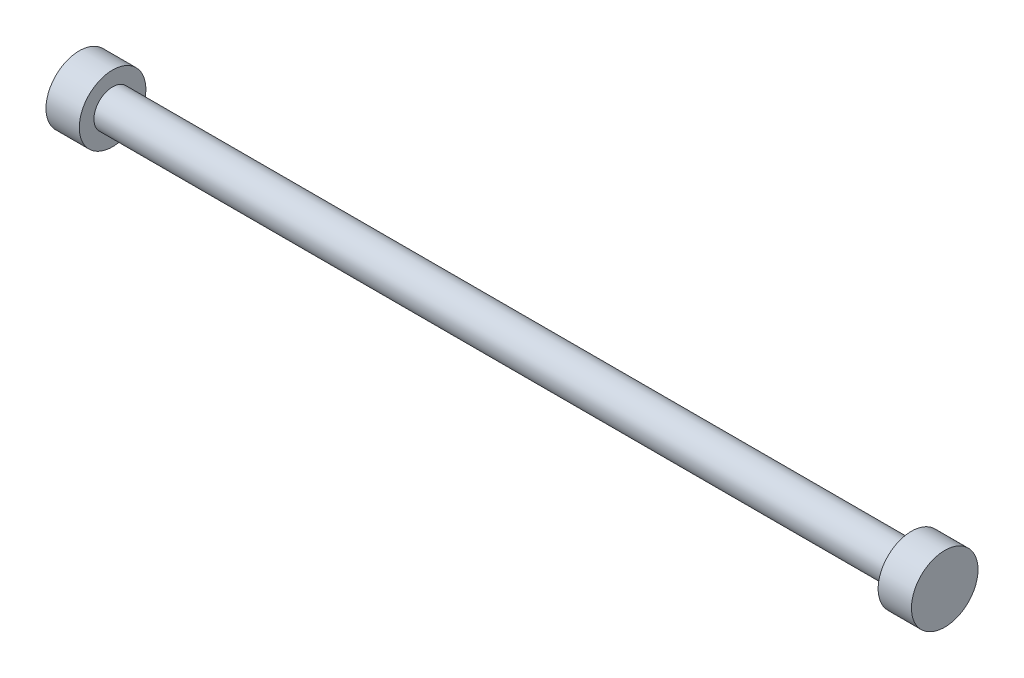
SolidWorks part; units mm, degrees
ref_plane "Front Plane" through (0, 0, 0) normal (0, 0, 1) x (1, 0, 0)
ref_plane "Top Plane" through (0, 0, 0) normal (0, 1, 0) x (1, 0, 0)
ref_plane "Right Plane" through (0, 0, 0) normal (1, 0, 0) x (0, 0, -1)
sketch "Sketch1" plane through (0, 0, 0) normal (1, 0, 0) x (0, 0, -1)
  circle A0 centre (0, 0) radius 1.778
  dimension "D1" = 3.556
extrude "Boss-Extrude1" add sketch "Sketch1" along normal blind 76.2
sketch "Sketch2" plane through (0, 0, 0) normal (-1, 0, 0) x (0, 0, 1)
  circle A0 centre (0, 0) radius 3.175
  dimension "D1" = 6.35
extrude "Boss-Extrude2" add sketch "Sketch2" along normal blind 3.175
sketch "Sketch3" plane through (76.2, 0, 0) normal (1, 0, 0) x (0, 0, -1)
  circle A0 centre (0, 0) radius 3.175
  dimension "D1" = 6.35
extrude "Boss-Extrude3" add sketch "Sketch3" along normal blind 3.175
